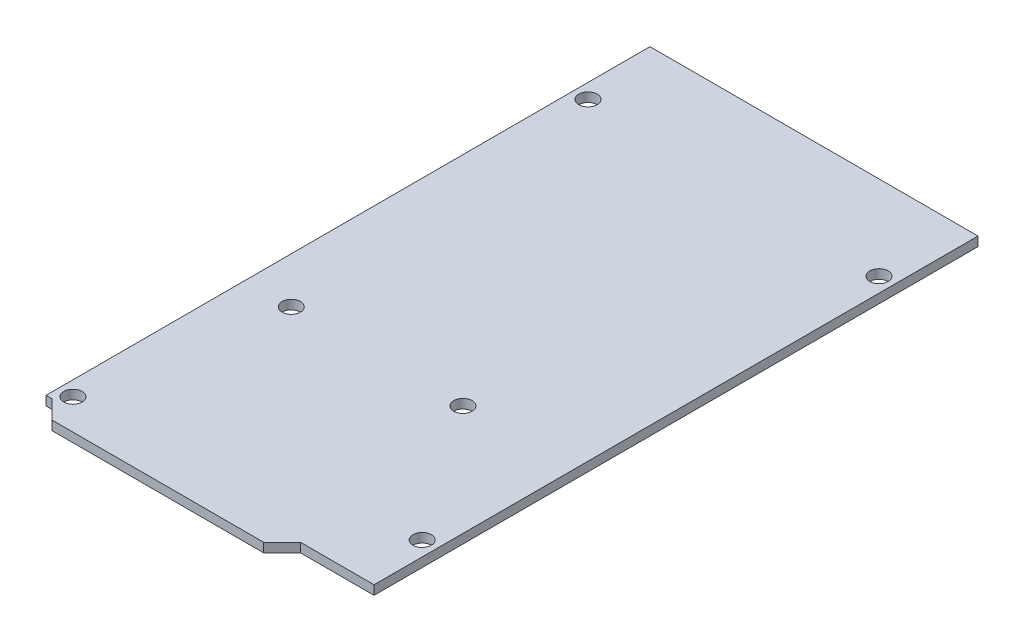
SolidWorks part; units mm, degrees
ref_plane "Front Plane" through (0, 0, 0) normal (0, 0, 1) x (1, 0, 0)
ref_plane "Top Plane" through (0, 0, 0) normal (0, 1, 0) x (1, 0, 0)
ref_plane "Right Plane" through (0, 0, 0) normal (1, 0, 0) x (0, 0, -1)
sketch "Sketch1" plane through (0, 0, 0) normal (0, 1, 0) x (1, 0, 0)
  line L0 (11.75, -50.75) -> (14.75, -47.75)
  line L1 (-26.75, -50.75) -> (26.75, -50.75)
  line L2 (-26.75, -50.75) -> (-26.75, 50.75)
  line L3 (-26.75, 50.75) -> (26.75, 50.75)
  line L4 (26.75, -50.75) -> (26.75, 50.75)
  line L5 (-26.75, -50.75) -> (26.75, 50.75) construction
  line L6 (-26.75, 50.75) -> (26.75, -50.75) construction
  line L7 (26.75, -50.75) -> (11.75, -50.75)
  line L8 (26.75, -50.75) -> (26.75, -47.75)
  line L9 (26.75, -47.75) -> (11.75, -47.75)
  line L10 (11.75, -50.75) -> (11.75, -47.75)
  line L11 (-22.75, -50.75) -> (-25.75, -47.75)
  line L12 (-26.75, -50.75) -> (-22.75, -50.75)
  line L13 (-26.75, -50.75) -> (-26.75, -47.75)
  line L14 (-26.75, -47.75) -> (-22.75, -47.75)
  line L15 (-22.75, -50.75) -> (-22.75, -47.75)
  line L16 (-26.75, 50.75) -> (-25.85, 50.75)
  line L17 (-25.85, 50.75) -> (-25.85, -44.25)
  line L18 (-25.85, -44.25) -> (-24.35, -44.25)
  line L19 (-24.35, -44.25) -> (-24.35, -45.75)
  line L20 (-25.85, 50.75) -> (-25.85, 38.25)
  line L21 (-25.85, 38.25) -> (-24.35, 38.25)
  line L22 (26.75, 50.75) -> (25.85, 50.75)
  line L23 (25.85, 50.75) -> (25.85, 37)
  line L24 (25.85, 37) -> (24.35, 37)
  line L25 (24.35, 35.5) -> (24.35, -36)
  line L26 (24.35, -36) -> (24.35, -37.5)
  line L27 (-20.75, 50.75) -> (-20.75, -13.75)
  line L28 (-26.75, 50.75) -> (-20.75, 50.75)
  line L29 (-20.75, -13.75) -> (-20.75, -15.25)
  line L30 (-20.75, -15.25) -> (-19.25, -15.25)
  line L31 (7.25, -15.25) -> (8.75, -15.25)
  line L32 (-17.75, -15.25) -> (7.25, -15.25)
  circle A1 centre (-24.35, -45.75) radius 1.5
  circle A2 centre (-24.35, 38.25) radius 1.5
  circle A3 centre (24.35, 37) radius 1.5
  circle A4 centre (24.35, -37.5) radius 1.5
  circle A7 centre (-19.25, -15.25) radius 1.5
  circle A8 centre (8.75, -15.25) radius 1.5
  point P0 (0, 0)
  dimension "D1" = 53.5
  dimension "D2" = 101.5
  dimension "D3" = 15
  dimension "D4" = 3
  dimension "D5" = 4
  dimension "D6" = 12.5
  dimension "D7" = 6
extrude "Boss-Extrude1" add sketch "Sketch1" along normal blind 1.5
